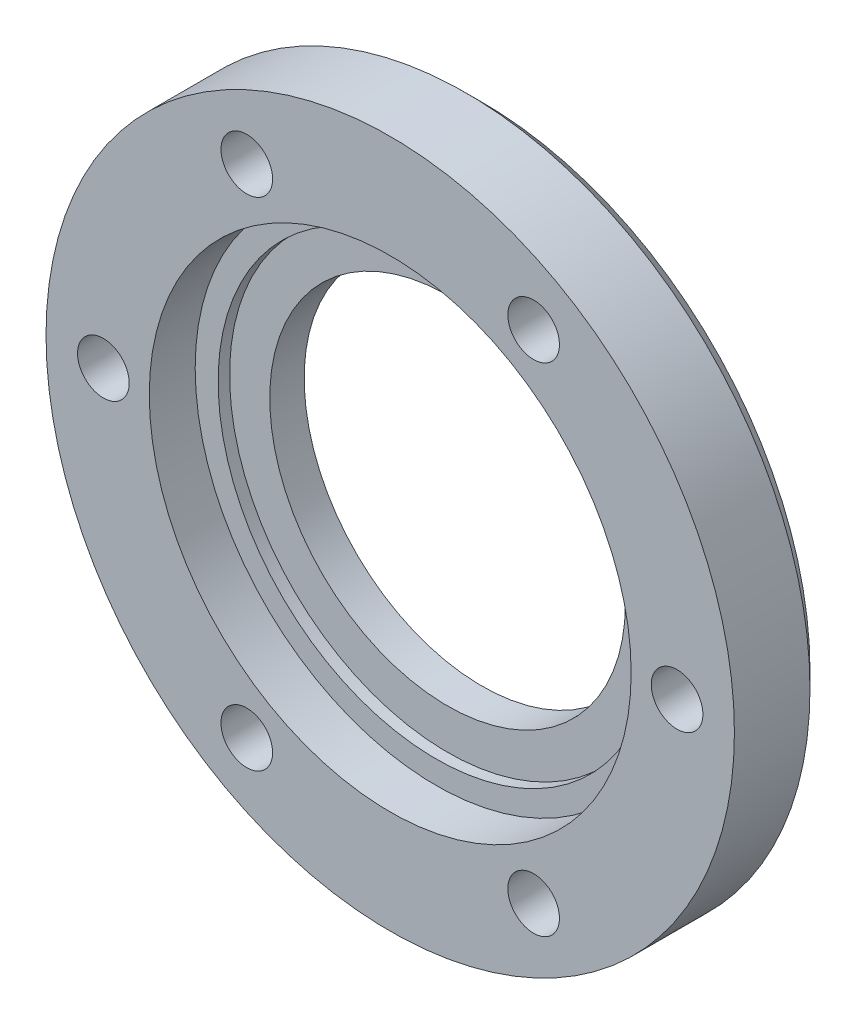
SolidWorks part; units mm, degrees
ref_plane "前视基准面" through (0, 0, 0) normal (0, 0, 1) x (1, 0, 0)
ref_plane "上视基准面" through (0, 0, 0) normal (0, 1, 0) x (1, 0, 0)
ref_plane "右视基准面" through (0, 0, 0) normal (1, 0, 0) x (0, 0, -1)
sketch "草图1" plane through (0, 0, 0) normal (0, 0, 1) x (1, 0, 0)
  circle A0 centre (0, 0) radius 30
  circle A1 centre (0, 0) radius 15.5
  dimension "D1" = 60
  dimension "D2" = 31
extrude "拉伸1" add sketch "草图1" along normal blind 8
sketch "草图2" plane through (0, 0, 8) normal (0, 0, 1) x (1, 0, 0)
  circle A0 centre (0, 0) radius 21
  dimension "D1" = 42
extrude "切除-拉伸1" cut sketch "草图2" against normal blind 4
sketch "草图3" plane through (0, 0, 4) normal (0, 0, 1) x (1, 0, 0)
  circle A0 centre (0, 0) radius 19
  dimension "D1" = 38
extrude "切除-拉伸2" cut sketch "草图3" against normal blind 1
sketch "草图4" plane through (0, 0, 0) normal (0, 0, -1) x (-1, 0, 0)
  line L0 (-500, -866.0254) -> (24500, 42435.2448) construction
  line L1 (500, -866.0254) -> (-24500, 42435.2448) construction
  line L2 (-1000, 0) -> (49000, 0) construction
  circle A0 centre (0, 0) radius 25 construction
  circle A1 centre (12.5, 21.6506) radius 2.25
  circle A2 centre (-12.5, 21.6506) radius 2.25
  circle A3 centre (-25, 0) radius 2.25
  circle A4 centre (-12.5, -21.6506) radius 2.25
  circle A5 centre (12.5, -21.6506) radius 2.25
  circle A6 centre (25, 0) radius 2.25
  dimension "D1" = 50
  dimension "D2" = 4.5
extrude "切除-拉伸3" cut sketch "草图4" against normal through all
sketch "草图5" plane through (0, 0, 0) normal (0, 0, -1) x (-1, 0, 0)
  circle A0 centre (-12.5, 21.6506) radius 3.5
  circle A1 centre (-25, 0) radius 3.5
  circle A2 centre (-12.5, -21.6506) radius 3.5
  circle A3 centre (12.5, -21.6506) radius 3.5
  circle A4 centre (25, 0) radius 3.5
  circle A5 centre (12.5, 21.6506) radius 3.5
  dimension "D1" = 7
extrude "切除-拉伸4" cut sketch "草图5" against normal blind 4
chamfer "倒角1" distance 1.414 angle 45 1 edges at (30, 0, 0)
